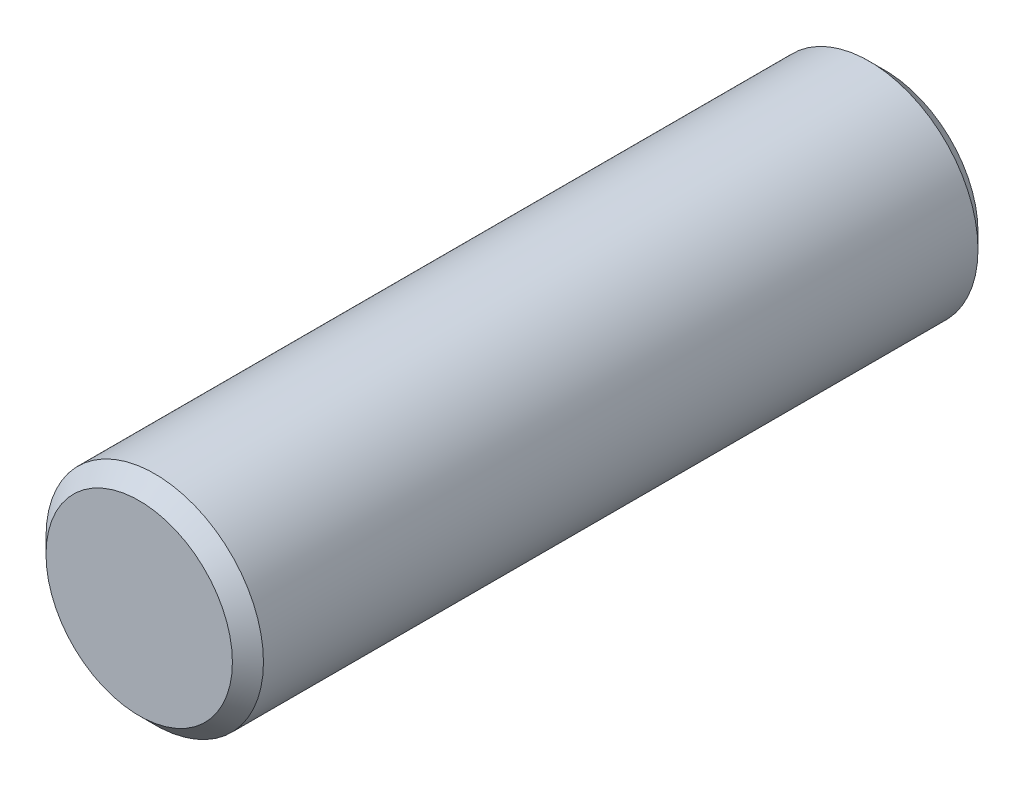
SolidWorks part; units mm, degrees
ref_plane "정면" through (0, 0, 0) normal (0, 0, 1) x (1, 0, 0)
ref_plane "윗면" through (0, 0, 0) normal (0, 1, 0) x (1, 0, 0)
ref_plane "우측면" through (0, 0, 0) normal (1, 0, 0) x (0, 0, -1)
sketch "스케치1" plane through (0, 0, 0) normal (0, 0, 1) x (1, 0, 0)
  circle A0 centre (0, 0) radius 3.5
  dimension "D1" = 7
extrude "보스-돌출1" add sketch "스케치1" along normal blind 24
chamfer "모따기1" distance 0.5 angle 45 2 edges at (3.5, 0, 24) (3.5, 0, 0)
